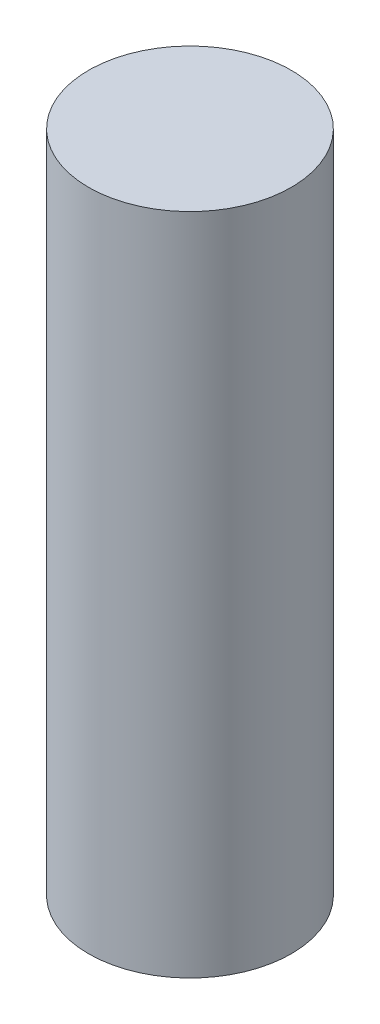
SolidWorks part; units mm, degrees
ref_plane "Front Plane" through (0, 0, 0) normal (0, 0, 1) x (1, 0, 0)
ref_plane "Top Plane" through (0, 0, 0) normal (0, 1, 0) x (1, 0, 0)
ref_plane "Right Plane" through (0, 0, 0) normal (1, 0, 0) x (0, 0, -1)
sketch "Sketch1" plane through (0, 0, 0) normal (0, 1, 0) x (1, 0, 0)
  circle A0 centre (0, 0) radius 16.5
  dimension "D1" = 33
extrude "Boss-Extrude1" add sketch "Sketch1" along normal blind 108
